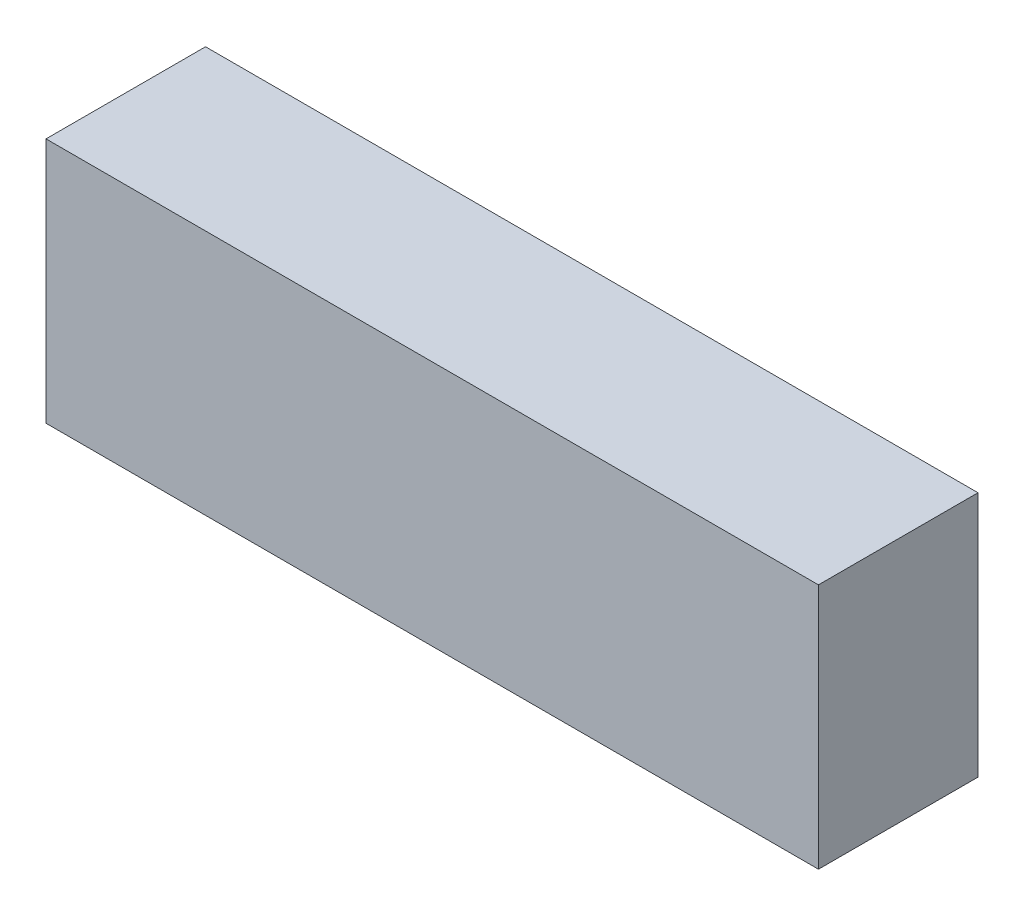
SolidWorks part; units mm, degrees
ref_plane "Front Plane" through (0, 0, 0) normal (0, 0, 1) x (1, 0, 0)
ref_plane "Top Plane" through (0, 0, 0) normal (0, 1, 0) x (1, 0, 0)
ref_plane "Right Plane" through (0, 0, 0) normal (1, 0, 0) x (0, 0, -1)
sketch "Sketch1" plane through (0, 0, 0) normal (0, 0, 1) x (1, 0, 0)
  line L1 (0, 0) -> (138, 0)
  line L2 (0, 0) -> (0, 44)
  line L3 (0, 44) -> (138, 44)
  line L4 (138, 0) -> (138, 44)
  dimension "D1" = 138
  dimension "D2" = 44
extrude "Boss-Extrude1" add sketch "Sketch1" along normal blind 28.5
